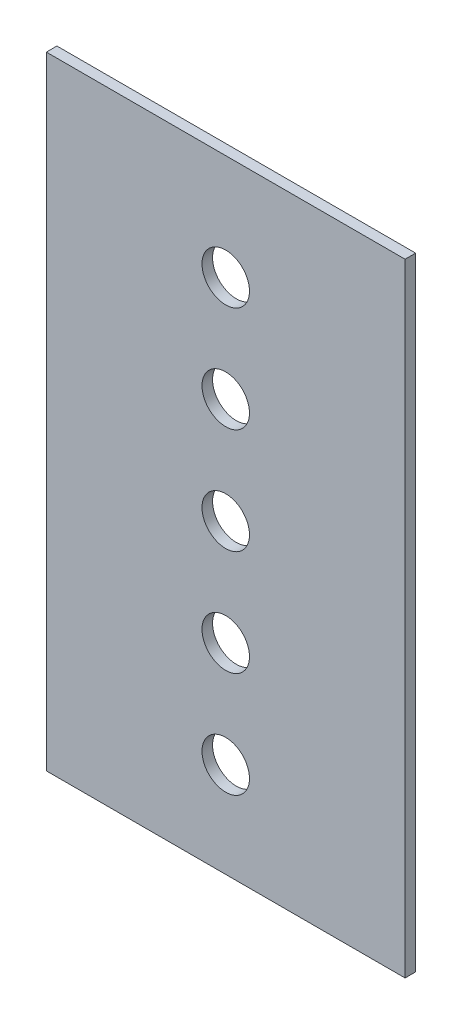
SolidWorks part; units mm, degrees
ref_plane "Front Plane" through (0, 0, 0) normal (0, 0, 1) x (1, 0, 0)
ref_plane "Top Plane" through (0, 0, 0) normal (0, 1, 0) x (1, 0, 0)
ref_plane "Right Plane" through (0, 0, 0) normal (1, 0, 0) x (0, 0, -1)
sketch "Sketch1" plane through (0, 0, 0) normal (0, 0, 1) x (1, 0, 0)
  line L0 (-44, 49.75) -> (-44, -9.25)
  line L1 (-10, -9.25) -> (-10, 49.75)
  line L4 (-10, 49.75) -> (-44, 49.75)
  line L6 (-44, -9.25) -> (-10, -9.25)
  circle A18 centre (-27, 39.75) radius 2.25
  circle A19 centre (-27, 29.75) radius 2.25
  circle A20 centre (-27, 19.75) radius 2.25
  circle A21 centre (-27, 9.7494) radius 2.25
  circle A22 centre (-27, -0.2506) radius 2.25
  dimension "D6" = 17
  dimension "D7" = 17
  dimension "D8" = 17
  dimension "D9" = 17
  dimension "D29" = 4.5
  dimension "D30" = 4.5
  dimension "D34" = 4.5
  dimension "D37" = 4.5
  dimension "D38" = 10
  dimension "D40" = 4.5
  dimension "D1" = 34
  dimension "D10" = 17
  dimension "D14" = 10
  dimension "D15" = 9.25
  dimension "D16" = 8.9994
  dimension "D28" = 10
  dimension "D31" = 10
  dimension "D33" = 10
  dimension "D36" = 10.0006
extrude "Boss-Extrude1" add sketch "Sketch1" along normal blind 1
